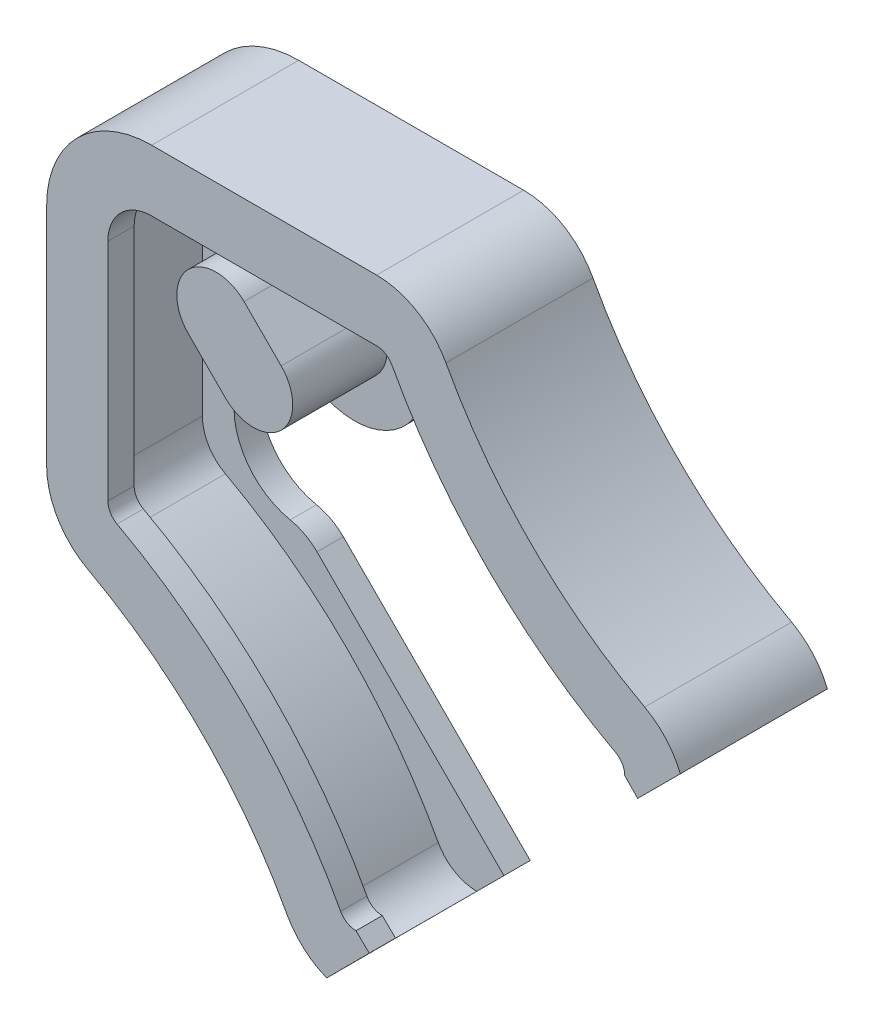
SolidWorks part; units mm, degrees
ref_plane "Alzado" through (0, 0, 0) normal (0, 0, 1) x (1, 0, 0)
ref_plane "Planta" through (0, 0, 0) normal (0, 1, 0) x (1, 0, 0)
ref_plane "Vista lateral" through (0, 0, 0) normal (1, 0, 0) x (0, 0, -1)
sketch "Croquis2" plane through (0, 0, 0) normal (0, 0, 1) x (1, 0, 0)
  line L0 (-679.5317, 350.2259) -> (-666.68, 350.2259)
  line L1 (-683.5317, 346.2259) -> (-683.5317, 333.3742)
  line L2 (-675.7535, 345.6297) -> (-673.6322, 343.5084)
  line L3 (-678.9355, 342.4477) -> (-676.8142, 340.3264)
  line L4 (-666.4753, 344.4195) -> (-666.4753, 342.4195)
  line L5 (-669.4753, 344.4195) -> (-669.4753, 342.4195)
  line L6 (-658.2253, 336.1695) -> (-660.2253, 336.1695)
  line L7 (-658.2253, 333.1695) -> (-660.2253, 333.1695)
  line L8 (-666.4753, 324.9195) -> (-666.4753, 326.9195)
  line L9 (-669.4753, 324.9195) -> (-669.4753, 326.9195)
  line L10 (-677.7253, 333.1695) -> (-675.7253, 333.1695)
  line L11 (-677.7253, 336.1695) -> (-675.7253, 336.1695)
  arc A0 (-664.4797, 348.9127) -> (-652.3179, 336.751) centre (-638.0759, 363.1548) ccw
  arc A1 (-664.4797, 348.9127) -> (-666.68, 350.2259) centre (-666.68, 347.7259) ccw
  arc A2 (-679.5317, 350.2259) -> (-683.5317, 346.2259) centre (-679.5317, 346.2259) ccw
  arc A3 (-683.5317, 333.3742) -> (-682.2185, 331.1739) centre (-681.0317, 333.3742) ccw
  arc A4 (-682.2185, 331.1739) -> (-670.0568, 319.0121) centre (-696.4606, 304.77) cw
  arc A5 (-670.0568, 319.0121) -> (-667.8565, 317.699) centre (-667.8565, 320.199) ccw
  arc A6 (-675.7535, 345.6297) -> (-678.9355, 342.4477) centre (-677.3445, 344.0387) ccw
  arc A7 (-673.6322, 343.5084) -> (-676.8142, 340.3264) centre (-675.2232, 341.9174) cw
  circle A8 centre (-667.9753, 334.6695) radius 4
  arc A9 (-669.4753, 344.4195) -> (-666.4753, 344.4195) centre (-667.9753, 344.4195) cw
  arc A10 (-669.4753, 342.4195) -> (-666.4753, 342.4195) centre (-667.9753, 342.4195) ccw
  arc A11 (-660.2253, 336.1695) -> (-660.2253, 333.1695) centre (-660.2253, 334.6695) ccw
  arc A12 (-658.2253, 336.1695) -> (-658.2253, 333.1695) centre (-658.2253, 334.6695) cw
  arc A13 (-666.4753, 326.9195) -> (-669.4753, 326.9195) centre (-667.9753, 326.9195) ccw
  arc A14 (-666.4753, 324.9195) -> (-669.4753, 324.9195) centre (-667.9753, 324.9195) cw
  arc A15 (-675.7253, 333.1695) -> (-675.7253, 336.1695) centre (-675.7253, 334.6695) ccw
  arc A16 (-677.7253, 333.1695) -> (-677.7253, 336.1695) centre (-677.7253, 334.6695) cw
  point P47 (-667.9753, 334.6695)
ref_plane "Plano1" through (0, 0, 0) normal (0, 0, 1) x (1, 0, 0)
sketch "Croquis4" plane through (0, 0, 0) normal (0, 0, 1) x (1, 0, 0)
  line L0 (-675.7535, 345.6297) -> (-673.6322, 343.5084)
  line L1 (-678.9355, 342.4477) -> (-676.8142, 340.3264)
  line L2 (-683.5317, 333.3742) -> (-683.5317, 346.2259)
  line L3 (-666.68, 350.2259) -> (-679.5317, 350.2259)
  line L4 (-669.4753, 344.4195) -> (-669.4753, 342.4195)
  line L5 (-666.4753, 342.4195) -> (-666.4753, 344.4195)
  line L6 (-658.2253, 336.1695) -> (-660.2253, 336.1695)
  line L7 (-660.2253, 333.1695) -> (-658.2253, 333.1695)
  line L8 (-666.4753, 324.9195) -> (-666.4753, 326.9195)
  line L9 (-669.4753, 326.9195) -> (-669.4753, 324.9195)
  line L10 (-677.7253, 333.1695) -> (-675.7253, 333.1695)
  line L11 (-675.7253, 336.1695) -> (-677.7253, 336.1695)
  line L12 (-682.3601, 349.0543) -> (-678.9355, 345.6297) construction
  line L13 (-667.8565, 317.699) -> (-651.0048, 334.5506)
  arc A0 (-683.5317, 346.2259) -> (-679.5317, 350.2259) centre (-679.5317, 346.2259) cw
  arc A1 (-678.9355, 342.4477) -> (-675.7535, 345.6297) centre (-677.3445, 344.0387) cw
  arc A2 (-676.8142, 340.3264) -> (-673.6322, 343.5084) centre (-675.2232, 341.9174) ccw
  arc A3 (-683.5317, 333.3742) -> (-682.2185, 331.1739) centre (-681.0317, 333.3742) ccw
  arc A4 (-682.2185, 331.1739) -> (-670.0568, 319.0121) centre (-696.4606, 304.77) cw
  arc A5 (-670.0568, 319.0121) -> (-667.8565, 317.699) centre (-667.8565, 320.199) ccw
  arc A6 (-666.68, 350.2259) -> (-664.4797, 348.9127) centre (-666.68, 347.7259) cw
  arc A7 (-664.4797, 348.9127) -> (-652.3179, 336.751) centre (-638.0759, 363.1548) ccw
  arc A8 (-669.4753, 344.4195) -> (-666.4753, 344.4195) centre (-667.9753, 344.4195) cw
  arc A9 (-669.4753, 342.4195) -> (-666.4753, 342.4195) centre (-667.9753, 342.4195) ccw
  circle A10 centre (-667.9753, 334.6695) radius 4
  arc A11 (-658.2253, 336.1695) -> (-658.2253, 333.1695) centre (-658.2253, 334.6695) cw
  arc A12 (-660.2253, 336.1695) -> (-660.2253, 333.1695) centre (-660.2253, 334.6695) ccw
  arc A13 (-666.4753, 324.9195) -> (-669.4753, 324.9195) centre (-667.9753, 324.9195) cw
  arc A14 (-666.4753, 326.9195) -> (-669.4753, 326.9195) centre (-667.9753, 326.9195) ccw
  arc A15 (-677.7253, 333.1695) -> (-677.7253, 336.1695) centre (-677.7253, 334.6695) cw
  arc A16 (-675.7253, 333.1695) -> (-675.7253, 336.1695) centre (-675.7253, 334.6695) ccw
  arc A17 (-652.3179, 336.751) -> (-651.0048, 334.5506) centre (-653.5048, 334.5506) cw
  point P68 (-667.9753, 334.6695)
  dimension "D1" = 4
extrude "Saliente-Extruir1" add sketch "Croquis4" along normal blind 1.5
sketch "Croquis5" plane through (0, 0, 0) normal (0, 0, -1) x (-1, 0, 0)
  line L8 (667.8565, 317.699) -> (669.5326, 316.0228)
  line L9 (651.0048, 334.5506) -> (649.3286, 336.2268)
  line L11 (685.5317, 333.3742) -> (685.5317, 346.2259)
  line L12 (649.1008, 333.6262) -> (666.9321, 315.7949)
  line L13 (679.5317, 352.2259) -> (666.68, 352.2259)
  line L14 (685.5317, 333.3742) -> (685.5317, 346.2259)
  line L16 (679.5317, 352.2259) -> (666.68, 352.2259)
  arc A36 (685.5317, 346.2259) -> (679.5317, 352.2259) centre (679.5317, 346.2259) ccw
  arc A37 (683.168, 329.4136) -> (685.5317, 333.3742) centre (681.0317, 333.3742) ccw
  arc A38 (683.168, 329.4136) -> (671.817, 318.0626) centre (696.4606, 304.77) ccw
  arc A39 (666.9321, 315.7949) -> (671.817, 318.0626) centre (667.8565, 320.199) ccw
  arc A40 (651.3685, 338.5112) -> (649.1008, 333.6262) centre (653.5048, 334.5506) ccw
  arc A41 (651.3685, 338.5112) -> (662.7194, 349.8622) centre (638.0759, 363.1548) ccw
  arc A42 (666.68, 352.2259) -> (662.7194, 349.8622) centre (666.68, 347.7259) ccw
  arc A43 (685.5317, 346.2259) -> (679.5317, 352.2259) centre (679.5317, 346.2259) ccw
  arc A44 (683.168, 329.4136) -> (685.5317, 333.3742) centre (681.0317, 333.3742) ccw
  arc A45 (683.168, 329.4136) -> (671.817, 318.0626) centre (696.4606, 304.77) ccw
  arc A46 (669.5326, 316.0228) -> (671.817, 318.0626) centre (667.8565, 320.199) ccw
  arc A47 (651.3685, 338.5112) -> (649.3286, 336.2268) centre (653.5048, 334.5506) ccw
  arc A48 (651.3685, 338.5112) -> (662.7194, 349.8622) centre (638.0759, 363.1548) ccw
  arc A49 (666.68, 352.2259) -> (662.7194, 349.8622) centre (666.68, 347.7259) ccw
  dimension "D1" = 2
extrude "Saliente-Extruir2" add sketch "Croquis5" against normal blind 6.9
sketch "Croquis6" plane through (0, 0, 6.9) normal (0, 0, 1) x (1, 0, 0)
  line L10 (-667.8565, 319.199) -> (-667.1002, 318.4653)
  line L11 (-669.5326, 316.0228) -> (-667.1002, 318.4653)
  line L12 (-666.68, 352.2259) -> (-679.5317, 352.2259)
  line L13 (-685.5317, 346.2259) -> (-685.5317, 333.3742)
  line L14 (-666.68, 352.2259) -> (-679.5317, 352.2259)
  line L15 (-685.5317, 346.2259) -> (-685.5317, 333.3742)
  line L16 (-652.504, 334.5514) -> (-651.7653, 333.7901)
  line L17 (-649.3286, 336.2268) -> (-651.7653, 333.7901)
  line L26 (-666.6796, 348.7263) -> (-679.5313, 348.7263)
  line L27 (-682.0313, 346.2263) -> (-682.0313, 333.3746)
  arc A42 (-649.3286, 336.2268) -> (-651.3685, 338.5112) centre (-653.5048, 334.5506) ccw
  arc A43 (-662.7194, 349.8622) -> (-651.3685, 338.5112) centre (-638.0759, 363.1548) ccw
  arc A44 (-662.7194, 349.8622) -> (-666.68, 352.2259) centre (-666.68, 347.7259) ccw
  arc A45 (-679.5317, 352.2259) -> (-685.5317, 346.2259) centre (-679.5317, 346.2259) ccw
  arc A46 (-685.5317, 333.3742) -> (-683.168, 329.4136) centre (-681.0317, 333.3742) ccw
  arc A47 (-671.817, 318.0626) -> (-683.168, 329.4136) centre (-696.4606, 304.77) ccw
  arc A48 (-671.817, 318.0626) -> (-669.5326, 316.0228) centre (-667.8565, 320.199) ccw
  arc A49 (-649.3286, 336.2268) -> (-651.3685, 338.5112) centre (-653.5048, 334.5506) ccw
  arc A50 (-662.7194, 349.8622) -> (-651.3685, 338.5112) centre (-638.0759, 363.1548) ccw
  arc A51 (-662.7194, 349.8622) -> (-666.68, 352.2259) centre (-666.68, 347.7259) ccw
  arc A52 (-679.5317, 352.2259) -> (-685.5317, 346.2259) centre (-679.5317, 346.2259) ccw
  arc A53 (-685.5317, 333.3742) -> (-683.168, 329.4136) centre (-681.0317, 333.3742) ccw
  arc A54 (-671.817, 318.0626) -> (-683.168, 329.4136) centre (-696.4606, 304.77) ccw
  arc A55 (-671.817, 318.0626) -> (-669.5326, 316.0228) centre (-667.8565, 320.199) ccw
  arc A73 (-652.504, 334.5514) -> (-653.0293, 335.4316) centre (-653.504, 334.5514) ccw
  arc A74 (-665.7995, 348.201) -> (-653.0293, 335.4316) centre (-638.0759, 363.1561) ccw
  arc A75 (-665.7995, 348.201) -> (-666.6796, 348.7263) centre (-666.6796, 347.7263) ccw
  arc A76 (-679.5313, 348.7263) -> (-682.0313, 346.2263) centre (-679.5313, 346.2263) ccw
  arc A77 (-682.0313, 333.3746) -> (-681.506, 332.4945) centre (-681.0313, 333.3746) ccw
  arc A78 (-668.7362, 319.7246) -> (-681.506, 332.4945) centre (-696.4602, 304.7704) ccw
  arc A79 (-668.7362, 319.7246) -> (-667.8565, 319.199) centre (-667.8559, 320.199) ccw
  dimension "D1" = 0
extrude "Saliente-Extruir3" add sketch "Croquis6" along normal blind 1.5
sketch "Croquis7" plane through (0, 0, 1.5) normal (0, 0, 1) x (1, 0, 0)
  line L0 (-677.7253, 330.6695) -> (-666.3056, 319.2498)
  line L1 (-667.8565, 317.699) -> (-651.0048, 334.5506) construction
  line L2 (-663.9753, 344.4195) -> (-652.5556, 332.9998)
  line L3 (-652.5556, 332.9998) -> (-666.3056, 319.2498)
  arc A28 (-663.9753, 344.4195) -> (-671.9753, 344.4195) centre (-667.9753, 344.4195) ccw
  arc A29 (-677.7253, 338.6695) -> (-677.7253, 330.6695) centre (-677.7253, 334.6695) ccw
  arc A30 (-677.7253, 338.6695) -> (-677.7253, 330.6695) centre (-677.7253, 334.6695) ccw
  arc A34 (-677.7253, 338.6695) -> (-671.9753, 344.4195) centre (-674.8503, 341.5445) ccw
  arc A40 (-658.2253, 330.6695) -> (-658.2253, 338.6695) centre (-658.2253, 334.6695) ccw [skipped]
  arc A41 (-671.9753, 324.9195) -> (-663.9753, 324.9195) centre (-667.9753, 324.9195) ccw [skipped]
  dimension "D1" = 2.5
  dimension "D2" = 4
extrude "Cortar-Extruir1" cut sketch "Croquis7" against normal up to vertex (1.5 mm away)
fillet "Redondeo1" radius 3 4 edges at (-663.9753, 344.4195, 0.75) (-677.7253, 330.6695, 0.75) (-677.7253, 338.6695, 0.75) (-671.9753, 344.4195, 0.75)
